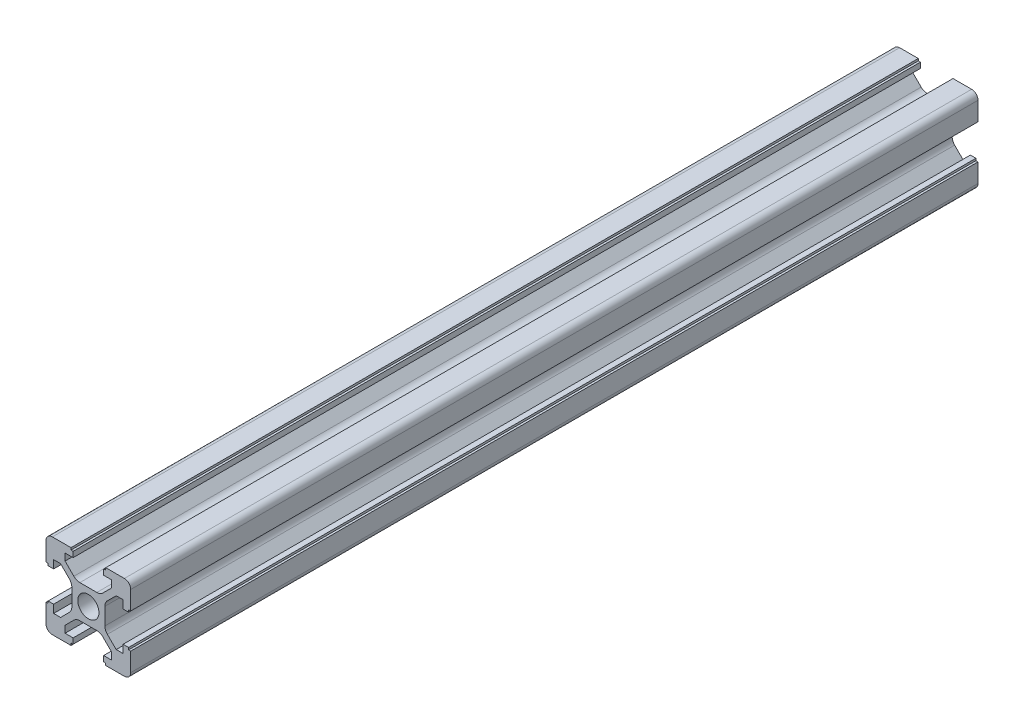
SolidWorks part; units mm, degrees
material "6063-O"
ref_plane "Front Plane" through (0, 0, 0) normal (0, 0, 1) x (1, 0, 0)
ref_plane "Top Plane" through (0, 0, 0) normal (0, 1, 0) x (1, 0, 0)
ref_plane "Right Plane" through (0, 0, 0) normal (1, 0, 0) x (0, 0, -1)
sketch "Sketch1" plane through (0, 0, 0) normal (0, 0, 1) x (1, 0, 0)
  line L0 (10, -4.1) -> (10, -8.5)
  line L1 (4.1, 10) -> (8.5, 10)
  line L2 (8.5, -10) -> (4.1, -10)
  line L3 (-8.5, -10) -> (-4.1, -10)
  line L4 (10, 8.5) -> (10, 4.1)
  line L7 (8.5, 10) -> (4.1, 10)
  line L8 (5.5, 6.5607) -> (3.4251, 4.4858)
  line L9 (8.5, 10) -> (4.1, 10)
  line L10 (3.9, 2.0109) -> (3.9, -2.0109)
  line L11 (2.0109, -3.9) -> (-2.0109, -3.9)
  line L12 (-3.9, -2.0109) -> (-3.9, 2.0109)
  line L13 (-2.0109, 3.9) -> (2.8393, 3.9)
  line L14 (2.5, 0) -> (22.2403, 0) construction
  line L15 (3.6, 9.5) -> (3.6, 8.2)
  line L16 (9.5, 3.6) -> (8.2, 3.6)
  line L17 (8.2, 3.6) -> (8.2, 5.5)
  line L18 (8.2, 5.5) -> (6.5607, 5.5)
  line L19 (10, -4.1) -> (10, -8.5)
  line L20 (4.1, 9.5) -> (3.6, 9.5)
  line L21 (4.1, 10) -> (4.1, 9.5)
  line L22 (8.5, 10) -> (4.1, 10)
  line L23 (10, 4.1) -> (9.5, 4.1)
  line L24 (9.5, 4.1) -> (9.5, 3.6)
  line L25 (5.5, 8.2) -> (5.5, 6.5607)
  line L26 (3.6, 8.2) -> (5.5, 8.2)
  line L27 (4.4858, 3.4251) -> (6.5607, 5.5)
  line L28 (10, -8.5) -> (10, -4.1)
  line L29 (6.5607, -5.5) -> (4.4858, -3.4251)
  line L30 (10, -8.5) -> (10, -4.1)
  line L31 (2.0109, -3.9) -> (-2.0109, -3.9)
  line L32 (3.9, 2.8393) -> (3.9, -2.0109)
  line L33 (9.5, -3.6) -> (8.2, -3.6)
  line L34 (3.6, -9.5) -> (3.6, -8.2)
  line L35 (3.6, -8.2) -> (5.5, -8.2)
  line L36 (5.5, -8.2) -> (5.5, -6.5607)
  line L37 (9.5, -4.1) -> (9.5, -3.6)
  line L38 (10, -4.1) -> (9.5, -4.1)
  line L39 (10, -8.5) -> (10, -4.1)
  line L40 (4.1, -10) -> (4.1, -9.5)
  line L41 (4.1, -9.5) -> (3.6, -9.5)
  line L42 (8.2, -5.5) -> (6.5607, -5.5)
  line L43 (8.2, -3.6) -> (8.2, -5.5)
  line L44 (3.4251, -4.4858) -> (5.5, -6.5607)
  line L45 (-4.1, -10) -> (-8.5, -10)
  line L46 (-10, -8.5) -> (-10, -4.1)
  line L47 (-8.5, -10) -> (-4.1, -10)
  line L48 (-5.5, -6.5607) -> (-3.4251, -4.4858)
  line L49 (-8.5, -10) -> (-4.1, -10)
  line L50 (-3.9, -2.0109) -> (-3.9, 2.0109)
  line L51 (2.0109, -3.9) -> (-2.0109, -3.9)
  line L52 (-3.6, -9.5) -> (-3.6, -8.2)
  line L53 (-9.5, -3.6) -> (-8.2, -3.6)
  line L54 (-8.2, -3.6) -> (-8.2, -5.5)
  line L55 (-8.2, -5.5) -> (-6.5607, -5.5)
  line L56 (-4.1, -9.5) -> (-3.6, -9.5)
  line L57 (-4.1, -10) -> (-4.1, -9.5)
  line L58 (-8.5, -10) -> (-4.1, -10)
  line L59 (-10, -4.1) -> (-9.5, -4.1)
  line L60 (-9.5, -4.1) -> (-9.5, -3.6)
  line L61 (-5.5, -8.2) -> (-5.5, -6.5607)
  line L62 (-3.6, -8.2) -> (-5.5, -8.2)
  line L63 (-4.4858, -3.4251) -> (-6.5607, -5.5)
  line L64 (-10, 4.1) -> (-10, 8.5)
  line L65 (-8.5, 10) -> (-4.1, 10)
  line L66 (-10, 8.5) -> (-10, 4.1)
  line L67 (-6.5607, 5.5) -> (-4.4858, 3.4251)
  line L68 (-10, 8.5) -> (-10, 4.1)
  line L69 (-2.0109, 3.9) -> (2.0109, 3.9)
  line L70 (-3.9, -2.0109) -> (-3.9, 2.0109)
  line L71 (-9.5, 3.6) -> (-8.2, 3.6)
  line L72 (-3.6, 9.5) -> (-3.6, 8.2)
  line L73 (-3.6, 8.2) -> (-5.5, 8.2)
  line L74 (-5.5, 8.2) -> (-5.5, 6.5607)
  line L75 (-9.5, 4.1) -> (-9.5, 3.6)
  line L76 (-10, 4.1) -> (-9.5, 4.1)
  line L77 (-10, 8.5) -> (-10, 4.1)
  line L78 (-4.1, 10) -> (-4.1, 9.5)
  line L79 (-4.1, 9.5) -> (-3.6, 9.5)
  line L80 (-8.2, 5.5) -> (-6.5607, 5.5)
  line L81 (-8.2, 3.6) -> (-8.2, 5.5)
  line L82 (-3.4251, 4.4858) -> (-5.5, 6.5607)
  line L83 (4.1, -10) -> (8.5, -10)
  arc A0 (2.0109, -3.9) -> (3.4251, -4.4858) centre (2.0109, -5.9) cw
  arc A1 (4.4858, -3.4251) -> (3.9, -2.0109) centre (5.9, -2.0109) cw
  arc A2 (3.9, 2.0109) -> (4.4858, 3.4251) centre (5.9, 2.0109) cw
  arc A3 (2.0109, 3.9) -> (3.4251, 4.4858) centre (2.0109, 5.9) ccw
  arc A4 (-2.0109, 3.9) -> (-3.4251, 4.4858) centre (-2.0109, 5.9) cw
  arc A5 (-4.4858, 3.4251) -> (-3.9, 2.0109) centre (-5.9, 2.0109) cw
  arc A6 (-3.4251, -4.4858) -> (-2.0109, -3.9) centre (-2.0109, -5.9) cw
  arc A7 (-3.9, -2.0109) -> (-4.4858, -3.4251) centre (-5.9, -2.0109) cw
  circle A8 centre (0, 0) radius 2.5
  arc A9 (-8.5, -10) -> (-10, -8.5) centre (-8.5, -8.5) cw
  arc A10 (-10, 8.5) -> (-8.5, 10) centre (-8.5, 8.5) cw
  arc A11 (8.5, 10) -> (10, 8.5) centre (8.5, 8.5) cw
  arc A12 (8.5, -10) -> (10, -8.5) centre (8.5, -8.5) ccw
  point P0 (0, 0)
  point P86 (0, 0)
  point P107 (10, -10)
  dimension "D3" = 2
  dimension "D5" = 5
  dimension "D2" = 1.5
  dimension "D8" = 1.5
  dimension "D6" = 4
  dimension "D7" = 6.1
  dimension "D11" = 0.5
  dimension "D12" = 0.5
extrude "Boss-Extrude2" add sketch "Sketch1" along normal blind 200
